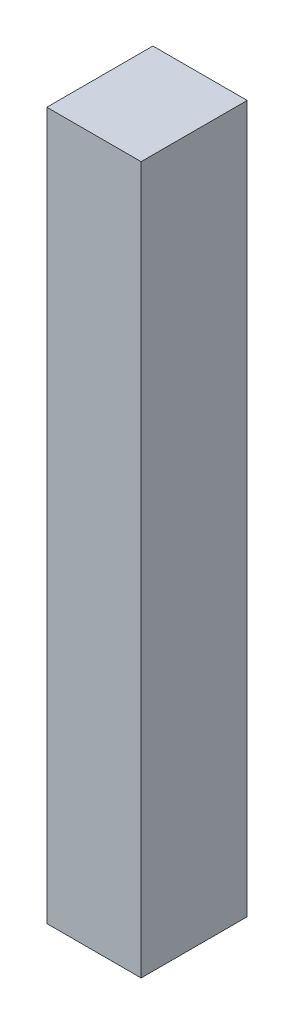
SolidWorks part; units mm, degrees
ref_plane "Front Plane" through (0, 0, 0) normal (0, 0, 1) x (1, 0, 0)
ref_plane "Top Plane" through (0, 0, 0) normal (0, 1, 0) x (1, 0, 0)
ref_plane "Right Plane" through (0, 0, 0) normal (1, 0, 0) x (0, 0, -1)
sketch "Sketch1" plane through (0, 0, 0) normal (0, 1, 0) x (1, 0, 0)
  line L1 (20, -22.5) -> (-20, -22.5)
  line L2 (20, -22.5) -> (20, 22.5)
  line L3 (20, 22.5) -> (-20, 22.5)
  line L4 (-20, -22.5) -> (-20, 22.5)
  line L5 (20, -22.5) -> (-20, 22.5) construction
  line L6 (20, 22.5) -> (-20, -22.5) construction
  point P0 (0, 0)
  dimension "D1" = 40
  dimension "D2" = 45
extrude "Boss-Extrude1" add sketch "Sketch1" along normal blind 300
